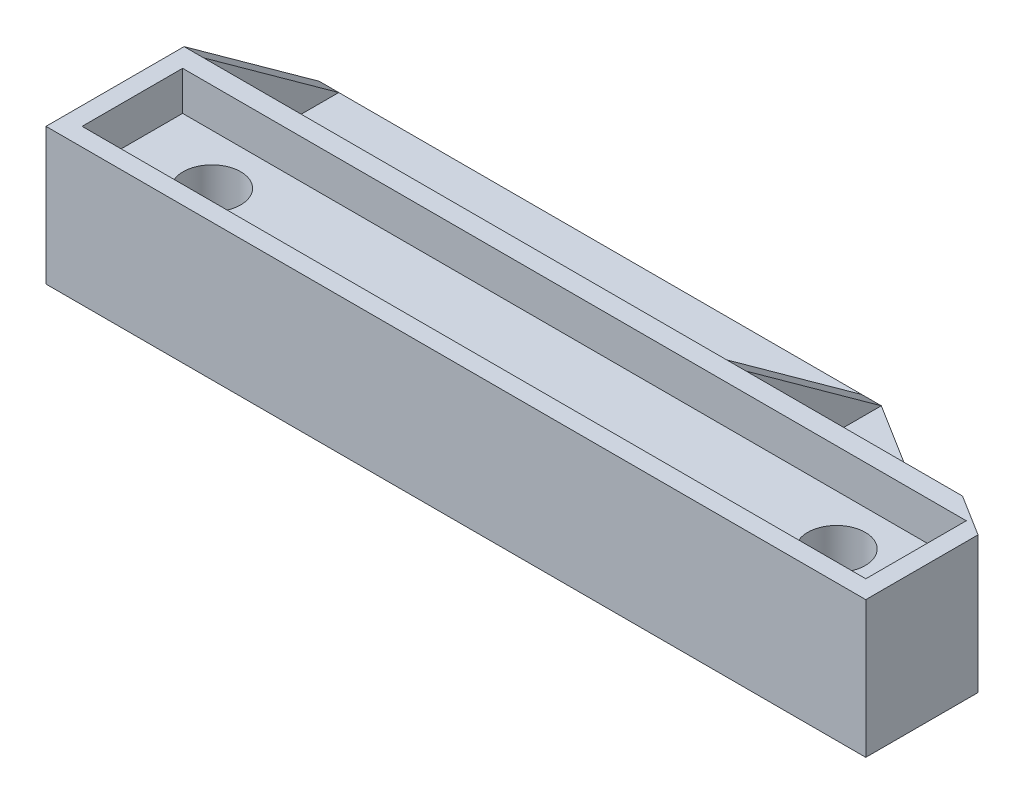
SolidWorks part; units mm, degrees
ref_plane "Front Plane" through (0, 0, 0) normal (0, 0, 1) x (1, 0, 0)
ref_plane "Top Plane" through (0, 0, 0) normal (0, 1, 0) x (1, 0, 0)
ref_plane "Right Plane" through (0, 0, 0) normal (1, 0, 0) x (0, 0, -1)
sketch "Sketch1" plane through (0, 0, 0) normal (0, 1, 0) x (1, 0, 0)
  line L0 (39.9996, 7) -> (42, 5.75)
  line L1 (0, 7) -> (39.9996, 7)
  line L2 (0, 7) -> (0, 0)
  line L3 (0, 0) -> (42, 0)
  line L4 (42, 5.75) -> (42, 0)
  dimension "D1" = 32
  dimension "D2" = 42
  dimension "D3" = 7
  dimension "D4" = 5.75
extrude "Riser" add sketch "Sketch1" along normal blind 7
sketch "Sketch2" plane through (0, 0, 0) normal (0, -1, 0) x (1, 0, 0)
  line L0 (0, -7) -> (0, 0) construction
  line L1 (21, 0) -> (21, -7) construction
  line L2 (0, 0) -> (42, 0) construction
  line L4 (39.9996, -7) -> (0, -7) construction
  circle A2 centre (5, -3.5) radius 1.475
  circle A3 centre (37, -3.5) radius 1.475
  point P2 (0, -3.5)
  dimension "D2" = 2.95
  dimension "D1" = 5
extrude "Mounting Holes" cut sketch "Sketch2" against normal through all
sketch "Sketch3" plane through (0, 7, 0) normal (0, 1, 0) x (1, 0, 0)
  line L12 (0.925, 6.075) -> (41.075, 6.075)
  line L13 (0.925, 6.075) -> (0.925, 0.925)
  line L14 (0.925, 0.925) -> (41.075, 0.925)
  line L15 (41.075, 6.075) -> (41.075, 0.925)
  line L17 (0, 7) -> (0, 0) construction
  line L18 (39.9996, 7) -> (0, 7) construction
  dimension "D1" = 5.15
  dimension "D2" = 40.15
  dimension "D3" = 0.925
  dimension "D4" = 0.925
extrude "Recess" cut sketch "Sketch3" against normal blind 2 contours L12 L15 L14 L13
sketch "Sketch4" plane through (0, 0, 0) normal (0, 1, 0) x (1, 0, 0)
  line L0 (16.7153, 21.5496) -> (46.0747, 3.2038) construction
  line L1 (0, 7) -> (39.9996, 7)
  line L2 (39.9996, 7) -> (28.7972, 14)
  line L3 (28.7972, 14) -> (0, 14)
  line L4 (0, 14) -> (0, 7)
  line L5 (42, 5.75) -> (39.9996, 7) construction
  dimension "D1" = 7
extrude "Flange" add sketch "Sketch4" along normal blind 7
sketch "Sketch5" plane through (0, 7, 0) normal (0, 1, 0) x (1, 0, 0)
  line L0 (1, 7.075) -> (1, 14)
  line L1 (28.7972, 14) -> (0, 14) construction
  line L2 (1, 14) -> (27.7972, 14)
  line L3 (27.7972, 14) -> (27.7972, 7.075)
  line L4 (27.7972, 7.075) -> (1, 7.075)
  line L11 (0, 14) -> (0, 0) construction
  line L12 (0.925, 6.075) -> (41.075, 6.075) construction
  line L13 (28.7972, 14) -> (28.7972, 7.075)
  line L14 (28.7972, 7.075) -> (39.8796, 7.075)
  line L15 (42, 5.75) -> (28.7972, 14) construction
  line L16 (39.8796, 7.075) -> (28.7972, 14)
  dimension "D1" = 1
  dimension "D2" = 1
  dimension "D3" = 1
extrude "Flange Cutout" cut sketch "Sketch5" against normal blind 5
sketch "Sketch7" plane through (27.7972, 0, 0) normal (-1, 0, 0) x (0, 0, 1)
  line L0 (-7.075, 7) -> (-14, 2)
  line L1 (-14, 2) -> (-14, 7)
  line L2 (-14, 7) -> (-7.075, 7)
extrude "Angle Cutout" cut sketch "Sketch7" against normal through all and the other way through all
chamfer "Flange Chamfer 1" distance 1 angle 45 1 edges at (14.3986, 2, -7.075)
chamfer "Flange Chamfer 2" distance 1 angle 45 1 edges at (34.3384, 2, -7.075)
